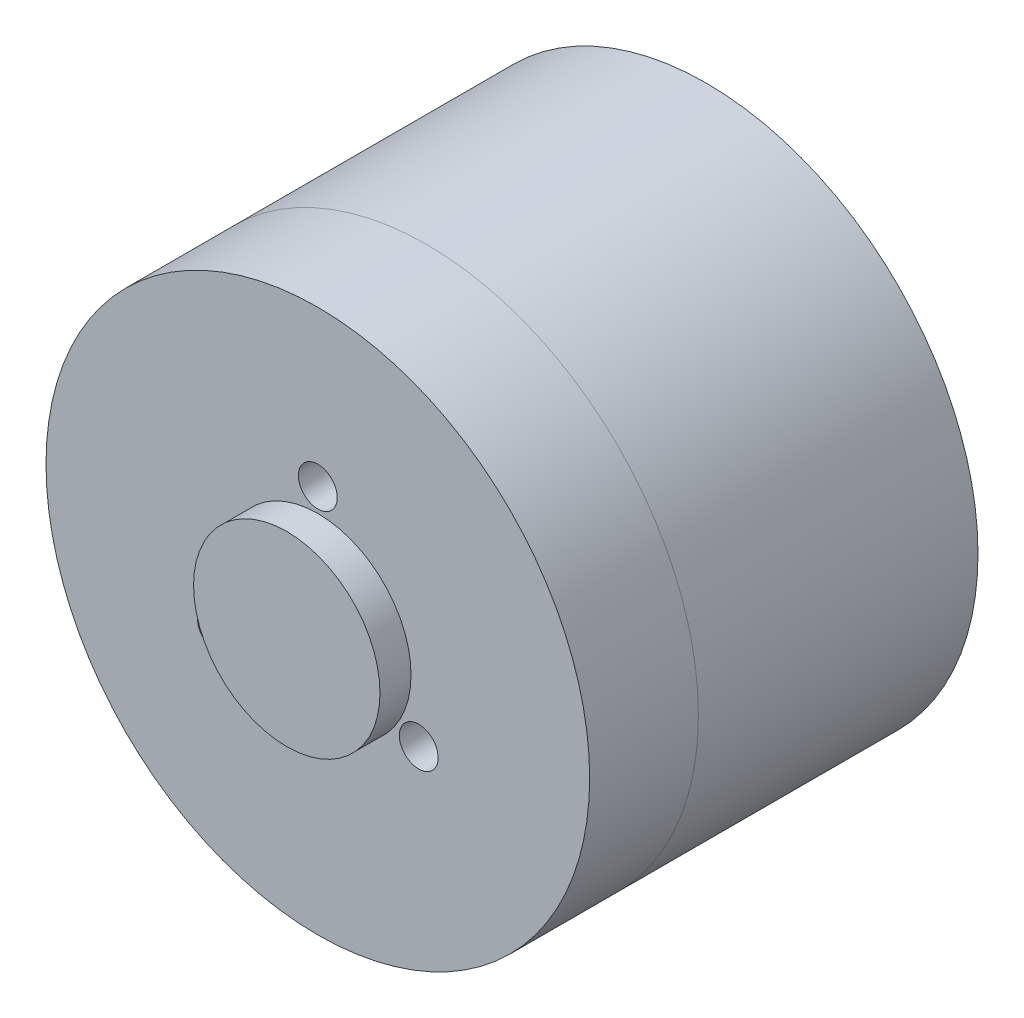
SolidWorks part; units mm, degrees
ref_plane "Front Plane" through (0, 0, 0) normal (0, 0, 1) x (1, 0, 0)
ref_plane "Top Plane" through (0, 0, 0) normal (0, 1, 0) x (1, 0, 0)
ref_plane "Right Plane" through (0, 0, 0) normal (1, 0, 0) x (0, 0, -1)
sketch "Sketch1" plane through (0, 0, 0) normal (0, 0, 1) x (1, 0, 0)
  circle A0 centre (0, 0) radius 17.5
  circle A1 centre (0, 0) radius 7.5 construction
  circle A2 centre (0, 7.5) radius 1.25
  circle A3 centre (6.4952, -3.75) radius 1.25
  circle A4 centre (-6.4952, -3.75) radius 1.25
  point P13 (0, 0)
  dimension "D1" = 35
  dimension "D2" = 15
  dimension "D3" = 2.5
  dimension "D5" = 120
  dimension "D6" = 120
  dimension "D4" = 3
extrude "Boss-Extrude1" add sketch "Sketch1" against normal blind 4
sketch "Sketch2" plane through (0, 0, -4) normal (0, 0, -1) x (-1, 0, 0)
  circle A0 centre (0, 0) radius 17.5
  circle A1 centre (0, 0) radius 15
  dimension "D1" = 35
  dimension "D2" = 30
extrude "Boss-Extrude2" add sketch "Sketch2" along normal blind 3
sketch "Sketch3" plane through (0, 0, 0) normal (0, 0, 1) x (1, 0, 0)
  circle A0 centre (0, 0) radius 6
  dimension "D1" = 12
extrude "Boss-Extrude3" add sketch "Sketch3" along normal blind 2
sketch "Sketch4" plane through (0, 0, -7) normal (0, 0, -1) x (-1, 0, 0)
  circle A0 centre (0, 0) radius 17.5
  circle A1 centre (0, 0) radius 15
  dimension "D1" = 35
  dimension "D2" = 30
extrude "Boss-Extrude4" add sketch "Sketch4" along normal blind 18 separate body
